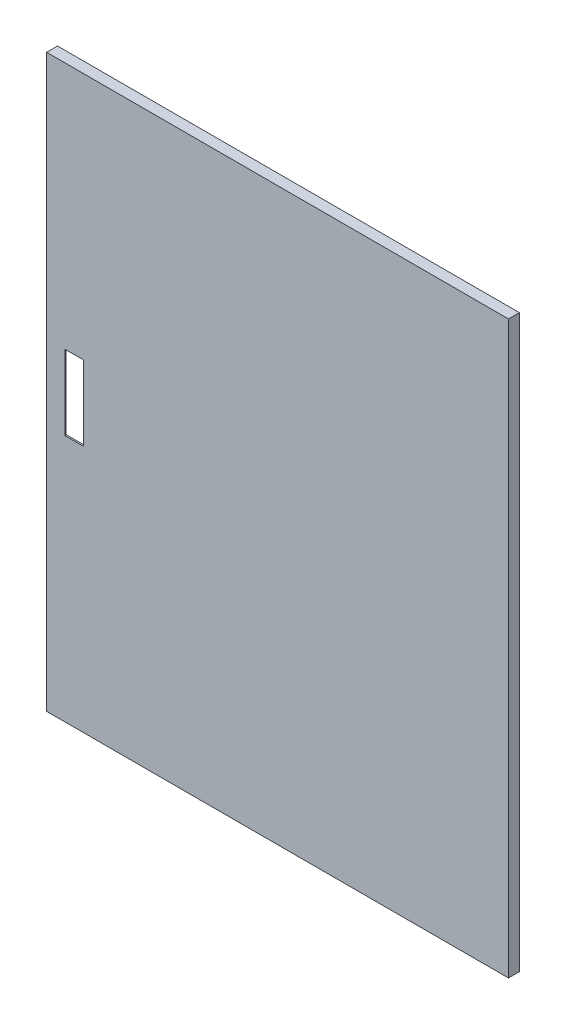
SolidWorks part; units mm, degrees
material "冷板"
ref_plane "前视基准面" through (0, 0, 0) normal (0, 0, 1) x (1, 0, 0)
ref_plane "上视基准面" through (0, 0, 0) normal (0, 1, 0) x (1, 0, 0)
ref_plane "右视基准面" through (0, 0, 0) normal (1, 0, 0) x (0, 0, -1)
sketch "草图1" plane through (0, 0, 0) normal (0, 0, 1) x (1, 0, 0)
  line L0 (0, 491.1739) -> (0, 0) construction
  line L1 (0, 0) -> (421.6954, 0) construction
  line L3 (-318, 393) -> (318, 393)
  line L4 (-318, 393) -> (-318, -393)
  line L5 (-318, -393) -> (318, -393)
  line L6 (318, 393) -> (318, -393)
  dimension "D1" = 636
  dimension "D2" = 786
extrude "凸台-拉伸1" add sketch "草图1" along normal blind 2
sketch "草图2" plane through (0, 0, 0) normal (0, 0, -1) x (-1, 0, 0)
  line L0 (0, 515.3034) -> (0, 0) construction
  line L1 (0, 0) -> (417.7311, 0) construction
  line L2 (316, -391) -> (316, 391)
  line L3 (316, 391) -> (-316, 391)
  line L4 (-316, 391) -> (-316, -391)
  line L5 (-316, -391) -> (316, -391)
  line L6 (318, -393) -> (318, 393)
  line L7 (318, 393) -> (-318, 393)
  line L8 (-318, 393) -> (-318, -393)
  line L9 (-318, -393) -> (318, -393)
  line L10 (318, -393) -> (318, 393)
  line L11 (318, 393) -> (-318, 393)
  line L12 (-318, 393) -> (-318, -393)
  line L13 (-318, -393) -> (318, -393)
  dimension "D1" = 0
  dimension "D2" = 2
extrude "凸台-拉伸2" add sketch "草图2" along normal blind 11
sketch "草图3" plane through (0, 0, -11) normal (0, 0, -1) x (-1, 0, 0)
  line L0 (-308, -383) -> (308, -383)
  line L1 (308, -383) -> (308, 383)
  line L2 (308, 383) -> (-308, 383)
  line L3 (-308, 383) -> (-308, -383)
  line L4 (-318, -393) -> (318, -393)
  line L5 (318, -393) -> (318, 393)
  line L6 (318, 393) -> (-318, 393)
  line L7 (-318, 393) -> (-318, -393)
  line L8 (-318, -393) -> (318, -393)
  line L9 (318, -393) -> (318, 393)
  line L10 (318, 393) -> (-318, 393)
  line L11 (-318, 393) -> (-318, -393)
  dimension "D1" = 0
  dimension "D2" = 10
extrude "凸台-拉伸3" add sketch "草图3" along normal blind 2
sketch "草图4" plane through (0, 0, 2) normal (0, 0, 1) x (1, 0, 0)
  line L0 (0, 473.4625) -> (0, 0) construction
  line L1 (0, 0) -> (-405.704, 0) construction
  line L2 (-318, 393) -> (-318, -393) construction
  line L3 (-293, 51.5) -> (-267, 51.5)
  line L4 (-293, 51.5) -> (-293, -51.5)
  line L5 (-293, -51.5) -> (-267, -51.5)
  line L6 (-267, 51.5) -> (-267, -51.5)
  dimension "D1" = 103
  dimension "D2" = 26
  dimension "D3" = 25
extrude "切除-拉伸1" cut sketch "草图4" against normal blind 10
